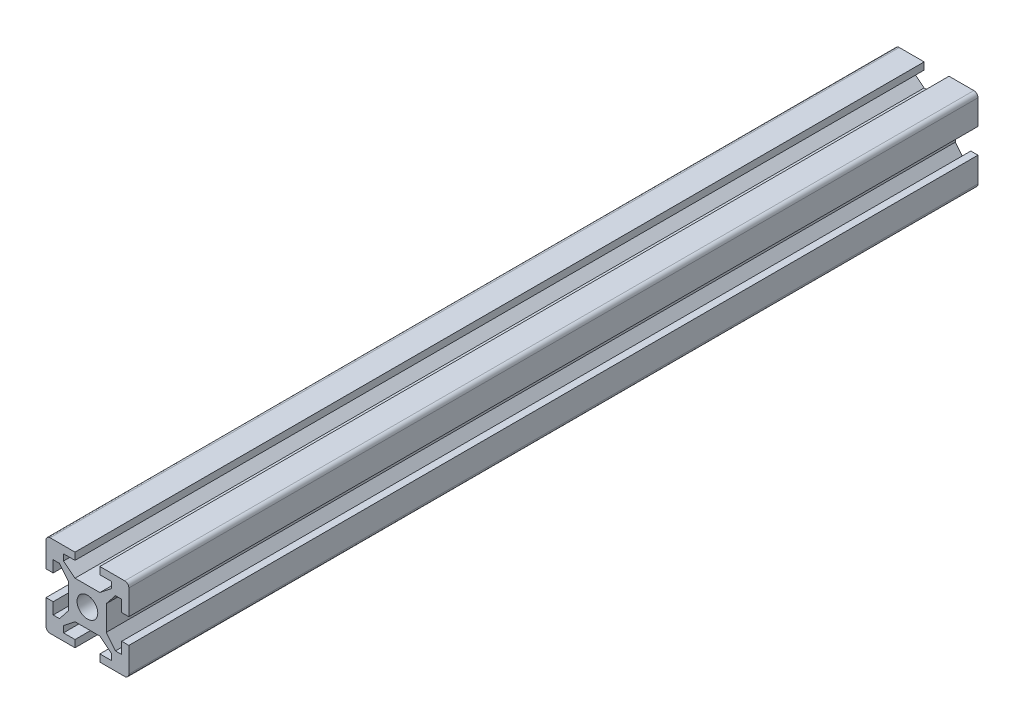
SolidWorks part; units mm, degrees
ref_plane "Front Plane" through (0, 0, 0) normal (0, 0, 1) x (1, 0, 0)
ref_plane "Top Plane" through (0, 0, 0) normal (0, 1, 0) x (1, 0, 0)
ref_plane "Right Plane" through (0, 0, 0) normal (1, 0, 0) x (0, 0, -1)
sketch "Sketch1" plane through (0, 0, 0) normal (0, 0, 1) x (1, 0, 0)
  line L18 (0, 0) -> (0, 20.5117) construction
  line L39 (-10, 10) -> (-3, 10)
  line L41 (10, 10) -> (3, 10)
  line L43 (-10, 10) -> (-10, 3)
  line L45 (-10, -10) -> (-10, -3)
  line L47 (-10, -10) -> (-3, -10)
  line L49 (3, -10) -> (10, -10)
  line L51 (10, -10) -> (10, -3)
  line L53 (10, 3) -> (10, 10)
  line L55 (-3, 10) -> (-3, 8.2726)
  line L56 (-3, 8.2726) -> (-5.7838, 8.2726)
  line L57 (-5.7838, 8.2726) -> (-5.7838, 6.748)
  line L58 (-5.7838, 6.748) -> (-3, 4.5508)
  line L59 (-3, 4.5508) -> (3, 4.5508)
  line L60 (3, 10) -> (3, 8.2726)
  line L61 (3, 8.2726) -> (5.7838, 8.2726)
  line L62 (5.7838, 8.2726) -> (5.7838, 6.748)
  line L63 (5.7838, 6.748) -> (3, 4.5508)
  line L64 (10, 3) -> (8.2726, 3)
  line L65 (8.2726, 3) -> (8.2726, 5.7838)
  line L66 (8.2726, 5.7838) -> (6.748, 5.7838)
  line L67 (10, -3) -> (8.2726, -3)
  line L68 (8.2726, -3) -> (8.2726, -5.7838)
  line L69 (8.2726, -5.7838) -> (6.748, -5.7838)
  line L70 (4.55, -2.9994) -> (4.55, 3.0006)
  line L71 (4.55, -2.9994) -> (6.748, -5.7838)
  line L72 (4.55, 3.0006) -> (6.748, 5.7838)
  line L73 (3, -10) -> (3, -8.2726)
  line L74 (3, -8.2726) -> (5.7838, -8.2726)
  line L75 (5.7838, -8.2726) -> (5.7838, -6.748)
  line L76 (-3, -10) -> (-3, -8.2726)
  line L77 (-3, -8.2726) -> (-5.7838, -8.2726)
  line L78 (-5.7838, -8.2726) -> (-5.7838, -6.748)
  line L79 (2.9994, -4.55) -> (-3.0006, -4.55)
  line L80 (5.7838, -6.748) -> (2.9994, -4.55)
  line L81 (-5.7838, -6.748) -> (-3.0006, -4.55)
  line L82 (-10, -3) -> (-8.2726, -3)
  line L83 (-8.2726, -3) -> (-8.2726, -5.7838)
  line L84 (-8.2726, -5.7838) -> (-6.748, -5.7838)
  line L85 (-10, 3) -> (-8.2726, 3)
  line L86 (-8.2726, 3) -> (-8.2726, 5.7838)
  line L87 (-8.2726, 5.7838) -> (-6.748, 5.7838)
  line L88 (-4.55, -3.0006) -> (-4.55, 2.9994)
  line L89 (-6.748, -5.7838) -> (-4.55, -3.0006)
  line L90 (-4.55, 2.9994) -> (-6.748, 5.7838)
  dimension "D9" = 7
  dimension "D17" = 2.7838
  dimension "D1" = 20
  dimension "D2" = 20
  dimension "D3" = 10
  dimension "D4" = 10
  dimension "D5" = 7
  dimension "D6" = 7
  dimension "D7" = 7
  dimension "D8" = 7
  dimension "D10" = 7
  dimension "D11" = 7
  dimension "D12" = 7
  dimension "D13" = 6
  dimension "D14" = 3
  dimension "D15" = 3.5464
  dimension "D16" = 1.5246
  dimension "D18" = 1.7274
  dimension "D19" = 4.55
  dimension "D20" = 4.55
  dimension "D21" = 4.55
  dimension "D22" = 10
  dimension "D23" = 10
  dimension "D24" = 10
  dimension "D25" = 10
  dimension "D26" = 10
  dimension "D27" = 10
  dimension "D28" = 6
  dimension "D29" = 6
  dimension "D30" = 6
  dimension "D31" = 6
extrude "Boss-Extrude1" add sketch "Sketch1" along normal mid plane 205
sketch "Sketch2" plane through (0, 0, 102.5) normal (0, 0, 1) x (1, 0, 0)
  circle A0 centre (0, 0) radius 2.5
  dimension "D1" = 5
extrude "Cut-Extrude1" cut sketch "Sketch2" against normal through all both and the other way through all
fillet "Fillet1" radius 1 4 edges at (-10, -10, 0) (10, -10, 0) (10, 10, 0) (-10, 10, 0)
